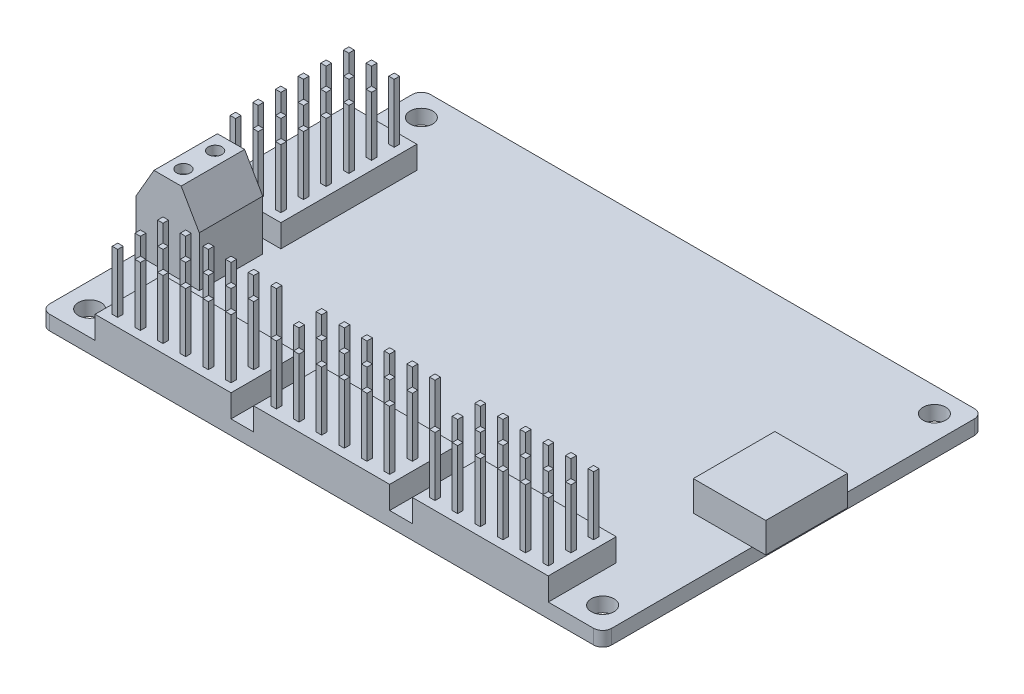
SolidWorks part; units mm, degrees
material "SERVO2040_AVG"
ref_plane "Front Plane" through (0, 0, 0) normal (0, 0, 1) x (1, 0, 0)
ref_plane "Top Plane" through (0, 0, 0) normal (0, 1, 0) x (1, 0, 0)
ref_plane "Right Plane" through (0, 0, 0) normal (1, 0, 0) x (0, 0, -1)
sketch "Sketch1" plane through (0, 0, 0) normal (0, 1, 0) x (1, 0, 0)
  line L0 (0, 0) -> (0, 50000) construction
  line L1 (-31, -21) -> (31, -21)
  line L2 (-31, -21) -> (-31, 21)
  line L3 (-31, 21) -> (31, 21)
  line L4 (31, -21) -> (31, 21)
  line L5 (-31, -21) -> (31, 21) construction
  line L6 (-31, 21) -> (31, -21) construction
  line L7 (0, 0) -> (50000, 0) construction
  circle A0 centre (-28.3, 18.3) radius 1.25
  circle A1 centre (28.3, 18.3) radius 1.25
  circle A2 centre (28.3, -18.3) radius 1.25
  circle A3 centre (-28.3, -18.3) radius 1.25
  point P0 (0, 0)
  dimension "D3" = 2.5
  dimension "D1" = 62
  dimension "D2" = 42
  dimension "D4" = 2.7
  dimension "D5" = 2.7
extrude "Boss-Extrude1" add sketch "Sketch1" along normal blind 1.6
fillet "Fillet1" radius 1 4 edges at (-31, 0.8, -21) (31, 0.8, -21) (31, 0.8, 21) (-31, 0.8, 21)
sketch "Sketch2" plane through (0, 1.6, 0) normal (0, 1, 0) x (1, 0, 0)
  line L0 (31, -20) -> (31, 20) construction
  line L1 (32.5, -4.5) -> (24.5, -4.5)
  line L2 (32.5, -4.5) -> (32.5, 4.5)
  line L3 (32.5, 4.5) -> (24.5, 4.5)
  line L4 (24.5, -4.5) -> (24.5, 4.5)
  line L5 (32.5, -4.5) -> (24.5, 4.5) construction
  line L6 (32.5, 4.5) -> (24.5, -4.5) construction
  point P0 (28.5, 0)
  dimension "D1" = 1.5
  dimension "D2" = 9
  dimension "D3" = 8
extrude "Boss-Extrude2" add sketch "Sketch2" along normal blind 3.3
sketch "Sketch3" plane through (0, 1.6, 0) normal (0, 1, 0) x (1, 0, 0)
  line L0 (31, -20) -> (31, -4.5) construction
  line L1 (25, -13.5) -> (10, -13.5)
  line L2 (25, -13.5) -> (25, -21)
  line L3 (25, -21) -> (10, -21)
  line L4 (10, -13.5) -> (10, -21)
  line L5 (25, -13.5) -> (10, -21) construction
  line L6 (25, -21) -> (10, -13.5) construction
  line L7 (-30, -21) -> (30, -21) construction
  point P0 (17.5, -17.25)
  dimension "D1" = 15
  dimension "D2" = 7.5
  dimension "D3" = 6
extrude "Boss-Extrude3" add sketch "Sketch3" along normal blind 2.5
sketch "Sketch4" plane through (0, 4.1, 0) normal (0, 1, 0) x (1, 0, 0)
  line L0 (10, -21) -> (25, -21) construction
  line L1 (24.0518, -20.0518) -> (23.4482, -20.0518)
  line L2 (24.0518, -20.0518) -> (24.0518, -19.4482)
  line L3 (24.0518, -19.4482) -> (23.4482, -19.4482)
  line L4 (23.4482, -20.0518) -> (23.4482, -19.4482)
  line L5 (24.0518, -20.0518) -> (23.4482, -19.4482) construction
  line L6 (24.0518, -19.4482) -> (23.4482, -20.0518) construction
  line L7 (25, -21) -> (25, -13.5) construction
  point P0 (23.75, -19.75)
  dimension "D1" = 1.25
  dimension "D2" = 1.25
extrude "Boss-Extrude4" add sketch "Sketch4" along normal blind 6.5
pattern_linear "LPattern2" count 3 spacing 2.5 along (0, 0, -1) count 6 spacing 2.5 along (-1, 0, 0) of "Boss-Extrude4"
pattern_linear "LPattern3" count 3 spacing 17.5 along (-1, 0, 0) of "Boss-Extrude3", "Boss-Extrude4", "LPattern2"
sketch "Sketch5" plane through (0, 1.6, 0) normal (0, 1, 0) x (1, 0, 0)
  line L0 (-31, 20) -> (-31, -20) construction
  line L1 (-23.5, -2) -> (-31, -2)
  line L2 (-23.5, -2) -> (-23.5, 13)
  line L3 (-23.5, 13) -> (-31, 13)
  line L4 (-31, -2) -> (-31, 13)
  line L5 (-23.5, -2) -> (-31, 13) construction
  line L6 (-23.5, 13) -> (-31, -2) construction
  line L7 (30, 21) -> (-30, 21) construction
  point P0 (-27.25, 5.5)
  dimension "D1" = 15
  dimension "D2" = 7.5
  dimension "D3" = 8
extrude "Boss-Extrude5" add sketch "Sketch5" along normal up to surface (2.5 mm away) up to face at (-21.25, 4.1, 14.75)
sketch "Sketch6" plane through (0, 1.6, 0) normal (0, 1, 0) x (1, 0, 0)
  line L0 (-31, -2) -> (-31, -20) construction
  line L1 (-24, -10.5) -> (-31, -10.5)
  line L2 (-24, -10.5) -> (-24, -3.5)
  line L3 (-24, -3.5) -> (-31, -3.5)
  line L4 (-31, -10.5) -> (-31, -3.5)
  line L5 (-24, -10.5) -> (-31, -3.5) construction
  line L6 (-24, -3.5) -> (-31, -10.5) construction
  line L7 (-23.5, -2) -> (-31, -2) construction
  point P0 (-27.5, -7)
  dimension "D1" = 7
  dimension "D2" = 7
  dimension "D3" = 1.5
extrude "Boss-Extrude6" add sketch "Sketch6" along normal blind 9
chamfer "Chamfer1" distance 2 angle 60 2 edges at (-31, 10.6, 7) (-24, 10.6, 7)
sketch "Sketch7" plane through (0, 10.6, 0) normal (0, 1, 0) x (1, 0, 0)
  line L0 (-27.5, -10.5) -> (-27.5, 49989.5) construction
  line L1 (-31, -10.5) -> (-24, -10.5) construction
  line L2 (-31, -7) -> (-50031, -7) construction
  line L3 (-31, -10.5) -> (-31, -3.5) construction
  circle A0 centre (-27.5, -8.75) radius 0.75
  circle A1 centre (-27.5, -5.25) radius 0.75
  point P8 (-27.5, -10.5)
  point P15 (-31, -7)
  dimension "D1" = 1.5
  dimension "D2" = 1.75
sketch "Sketch8" plane through (0, 4.1, 0) normal (0, 1, 0) x (1, 0, 0)
  line L0 (-23.5, -2) -> (-31, -2) construction
  line L1 (-29.45, -0.45) -> (-30.05, -0.45)
  line L2 (-29.45, -0.45) -> (-29.45, -1.05)
  line L3 (-29.45, -1.05) -> (-30.05, -1.05)
  line L4 (-30.05, -0.45) -> (-30.05, -1.05)
  line L5 (-29.45, -0.45) -> (-30.05, -1.05) construction
  line L6 (-29.45, -1.05) -> (-30.05, -0.45) construction
  line L7 (-31, -2) -> (-31, 13) construction
  point P0 (-29.75, -0.75)
  dimension "D1" = 0.6
  dimension "D2" = 1.25
  dimension "D3" = 1.25
extrude "Boss-Extrude7" add sketch "Sketch8" along normal blind 6.5
extrude "Cut-Extrude1" cut sketch "Sketch7" against normal blind 1
pattern_linear "LPattern4" count 3 spacing 2.5 along (1, 0, 0) count 6 spacing 2.5 along (0, 0, -1) of "Boss-Extrude7"
